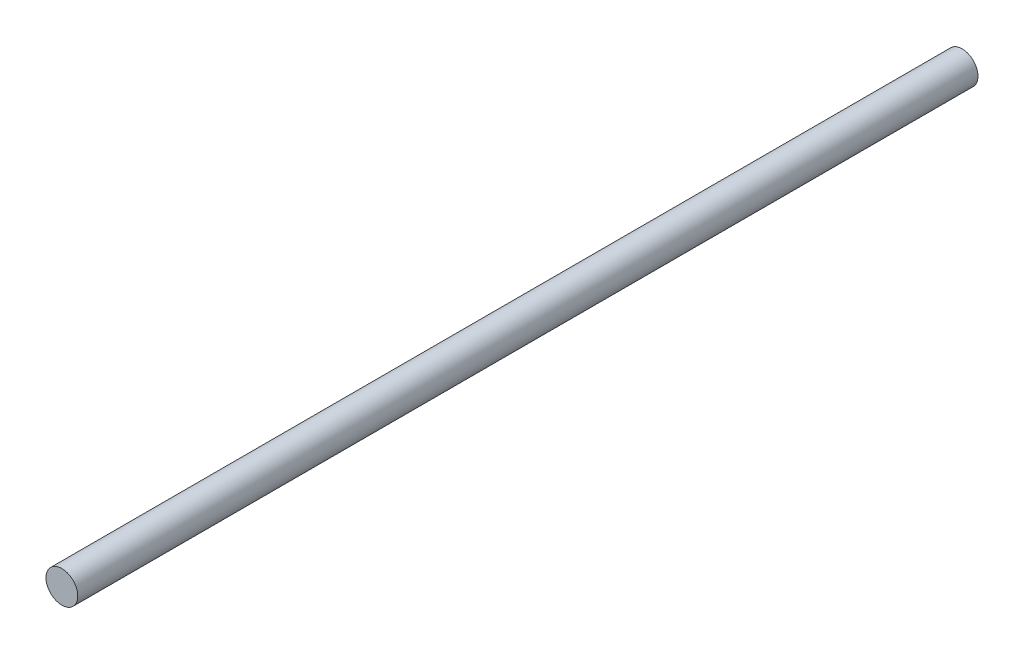
SolidWorks part; units mm, degrees
ref_plane "Front Plane" through (0, 0, 0) normal (0, 0, 1) x (1, 0, 0)
ref_plane "Top Plane" through (0, 0, 0) normal (0, 1, 0) x (1, 0, 0)
ref_plane "Right Plane" through (0, 0, 0) normal (1, 0, 0) x (0, 0, -1)
sketch "Sketch1" plane through (0, 0, 0) normal (0, 0, 1) x (1, 0, 0)
  circle A0 centre (0, 0) radius 6
  dimension "D1" = 12
extrude "Boss-Extrude1" add sketch "Sketch1" along normal blind 340
